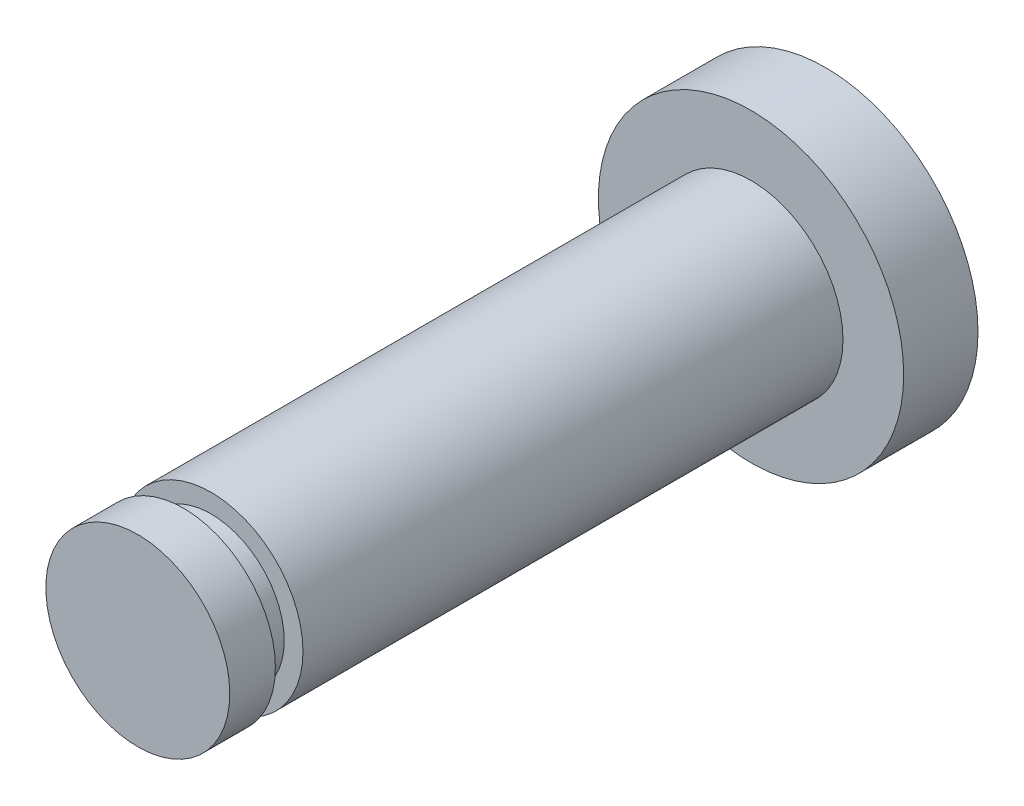
SolidWorks part; units mm, degrees
ref_plane "Front Plane" through (0, 0, 0) normal (0, 0, 1) x (1, 0, 0)
ref_plane "Top Plane" through (0, 0, 0) normal (0, 1, 0) x (1, 0, 0)
ref_plane "Right Plane" through (0, 0, 0) normal (1, 0, 0) x (0, 0, -1)
sketch "S01 - Smooth pin and end margin" plane through (0, 0, 0) normal (0, 0, 1) x (1, 0, 0)
  circle A0 centre (0, 0) radius 2.5
extrude "01 - Smooth pin and end margin" add sketch "S01 - Smooth pin and end margin" along normal blind 16.67 from offset 7.23
sketch "S02 - Clevis pin head" plane through (0, 0, 0) normal (0, 0, 1) x (1, 0, 0)
  circle A0 centre (0, 0) radius 4.15
extrude "02 - Clevis pin head" add sketch "S02 - Clevis pin head" along normal blind 2.02 from offset 9.25
sketch "S03 - DE-4 retaining groove" plane through (0, 0, 0) normal (0, 0, 1) x (1, 0, 0)
  circle A0 centre (0, 0) radius 2.6
  circle A1 centre (0, 0) radius 1.99
extrude "03 - DE-4 retaining groove" cut sketch "S03 - DE-4 retaining groove" along normal blind 0.75 from offset 7.45
